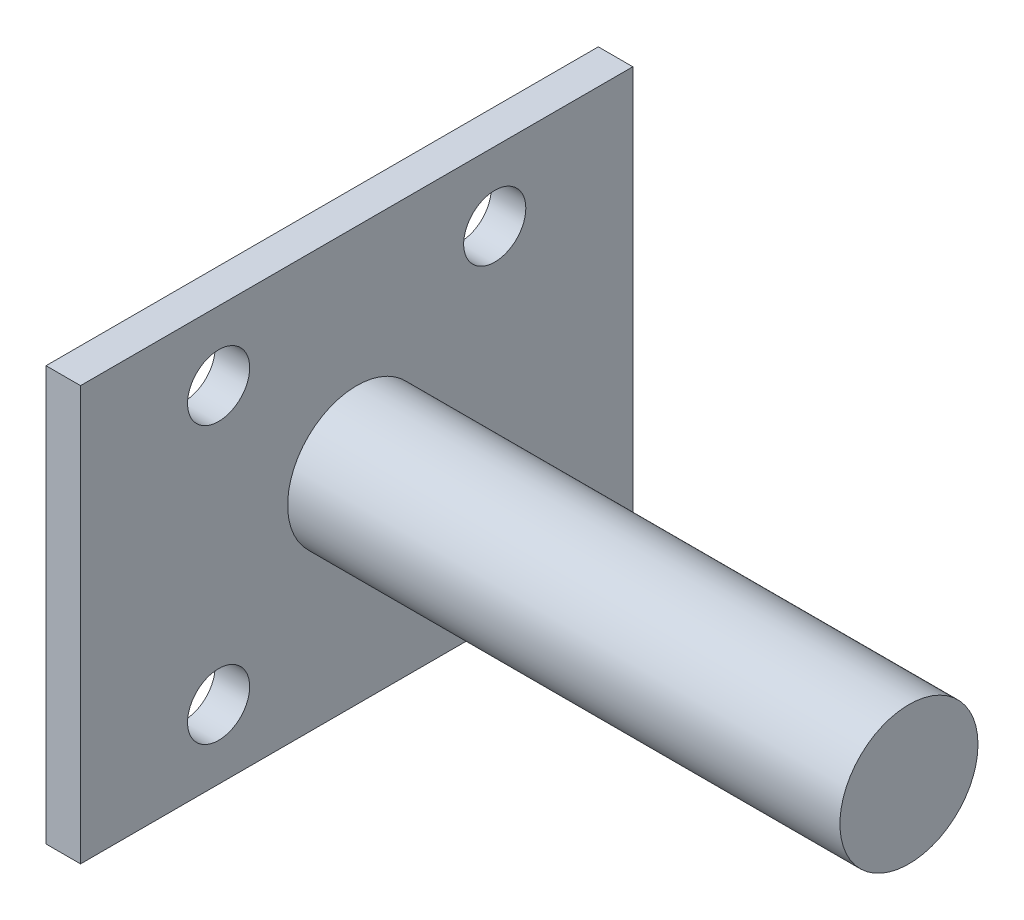
SolidWorks part; units mm, degrees
ref_plane "Front Plane" through (0, 0, 0) normal (0, 0, 1) x (1, 0, 0)
ref_plane "Top Plane" through (0, 0, 0) normal (0, 1, 0) x (1, 0, 0)
ref_plane "Right Plane" through (0, 0, 0) normal (1, 0, 0) x (0, 0, -1)
other "Configuration Table"
sketch "Sketch1" plane through (0, 0, 0) normal (1, 0, 0) x (0, 0, -1)
  line L1 (20, -15) -> (-20, -15)
  line L2 (20, -15) -> (20, 15)
  line L3 (20, 15) -> (-20, 15)
  line L4 (-20, -15) -> (-20, 15)
  line L5 (20, -15) -> (-20, 15) construction
  line L6 (20, 15) -> (-20, -15) construction
  point P0 (0, 0)
  dimension "D1" = 30
  dimension "D2" = 40
extrude "Boss-Extrude1" add sketch "Sketch1" along normal blind 2.5
sketch "Sketch2" plane through (2.5, 0, 0) normal (1, 0, 0) x (0, 0, -1)
  circle A0 centre (0, 0) radius 5
extrude "Boss-Extrude2" add sketch "Sketch2" along normal blind 40
sketch "Sketch3" plane through (2.5, 0, 0) normal (1, 0, 0) x (0, 0, -1)
  line L0 (-10, -15) -> (-10, 15) construction
  line L1 (-20, -15) -> (20, -15) construction
  line L2 (20, 15) -> (-20, 15) construction
  line L3 (10, -15) -> (10, 15) construction
  dimension "D1" = 10
  dimension "D2" = 10
sketch "Sketch4" plane through (2.5, 0, 0) normal (1, 0, 0) x (0, 0, -1)
  line L0 (-10, -15) -> (-10, 15) construction
  line L1 (10, -15) -> (10, 15) construction
  circle A0 centre (-10, 10) radius 2.25
  circle A1 centre (-10, -10) radius 2.25
  circle A2 centre (10, 10) radius 2.25
  circle A3 centre (10, -10) radius 2.25
  dimension "D1" = 5
  dimension "D2" = 5
extrude "Cut-Extrude1" cut sketch "Sketch4" against normal through all
